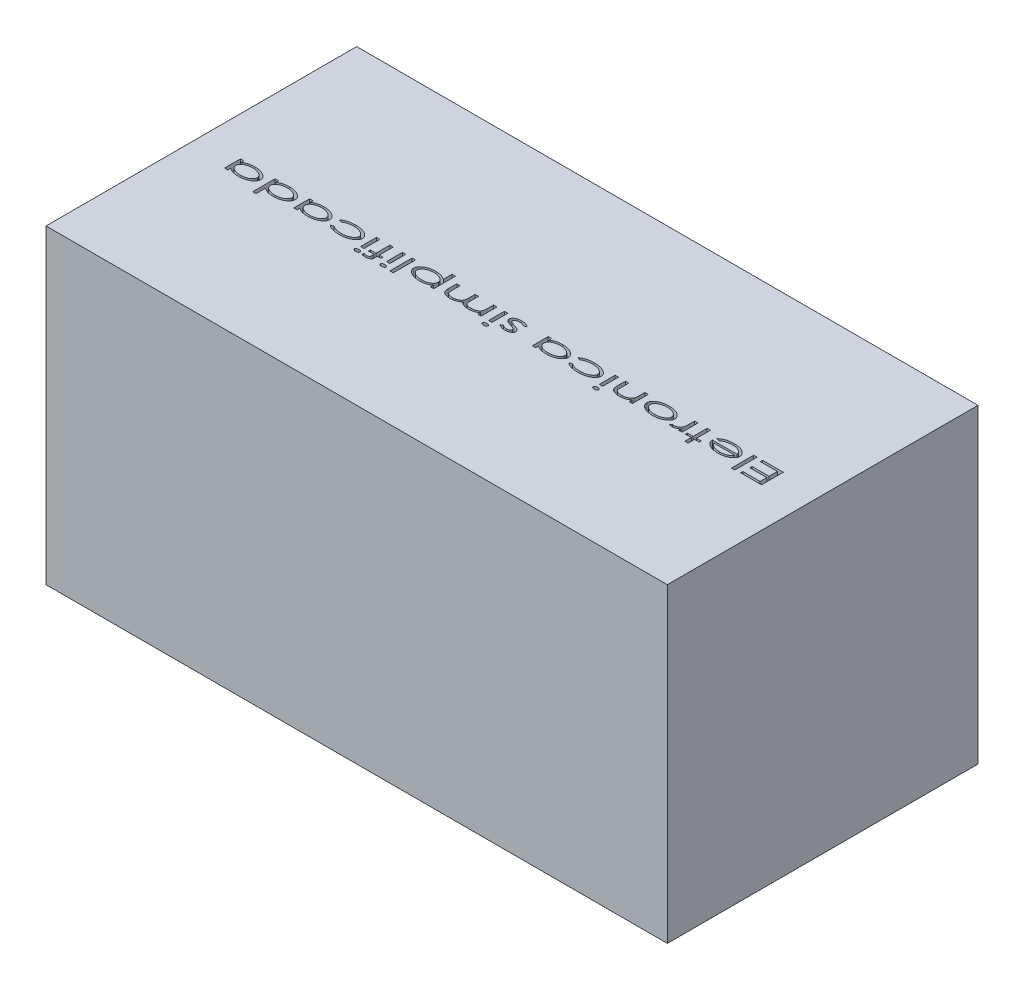
SolidWorks part; units mm, degrees
material "Eletronica simpificada 2025"
ref_plane "Plano frontal" through (0, 0, 0) normal (0, 0, 1) x (1, 0, 0)
ref_plane "Plano superior" through (0, 0, 0) normal (0, 1, 0) x (1, 0, 0)
ref_plane "Plano direito" through (0, 0, 0) normal (1, 0, 0) x (0, 0, -1)
sketch "Esboço1" plane through (0, 0, 0) normal (0, 0, 1) x (1, 0, 0)
  line L1 (-50, -25) -> (50, -25)
  line L2 (-50, -25) -> (-50, 25)
  line L3 (-50, 25) -> (50, 25)
  line L4 (50, -25) -> (50, 25)
  line L5 (-50, -25) -> (50, 25) construction
  line L6 (-50, 25) -> (50, -25) construction
  point P0 (0, 0)
  dimension "D1" = 100
  dimension "50" = 50
extrude "Ressalto-extrusão1" add sketch "Esboço1" along normal mid plane 50
sketch "Esboço2" plane through (0, 25, 0) normal (0, 1, 0) x (1, 0, 0)
  line L1 (50, -25) -> (50, 25) construction
  line L2 (50, 0) -> (-50, 0) construction
  line L3 (-50, -25) -> (-50, 25) construction
  text T0 "Eletronica simplificada" font "Century Gothic" height 3.5
extrude "Corte-extrusão1" cut sketch "Esboço2" against normal blind 3
